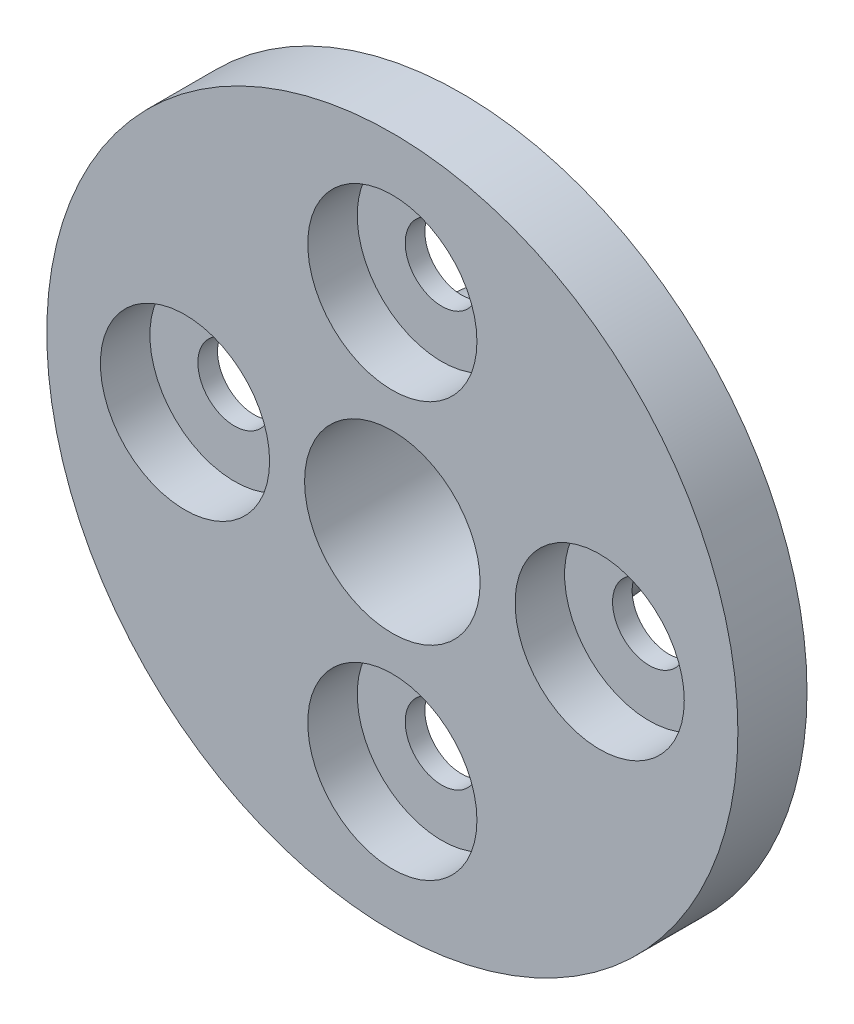
SolidWorks part; units mm, degrees
ref_plane "Alzado" through (0, 0, 0) normal (0, 0, 1) x (1, 0, 0)
ref_plane "Planta" through (0, 0, 0) normal (0, 1, 0) x (1, 0, 0)
ref_plane "Vista lateral" through (0, 0, 0) normal (1, 0, 0) x (0, 0, -1)
sketch "Sketch1" plane through (0, 0, 0) normal (0, 0, 1) x (1, 0, 0)
  circle A0 centre (0, 0) radius 6.35
  circle A1 centre (0, 0) radius 25
  dimension "D1" = 12.7
  dimension "D2" = 50
extrude "Boss-Extrude1" add sketch "Sketch1" along normal blind 5
sketch "Sketch2" plane through (0, 0, 0) normal (0, 0, -1) x (-1, 0, 0)
  circle A0 centre (0, 0) radius 6.35 construction
  circle A1 centre (0, 0) radius 6.35
  circle A2 centre (0, 0) radius 9
  dimension "D1" = 18
extrude "Boss-Extrude2" add sketch "Sketch2" along normal blind 6
hole_wizard "CBORE for M5 Hex Head Bolt1" positions "Sketch3" profile "Sketch5" counterbore size "M5" standard "ANSI Metric"
sketch "Sketch3" plane through (0, 0, 5) normal (0, 0, 1) x (1, 0, 0)
  circle A0 centre (0, 0) radius 15
  point P0 (0, 15)
  point P2 (15, 0)
  point P4 (0, -15)
  point P6 (-15, 0)
  point P14 (15, 0)
  point P15 (0, 15)
  point P16 (-15, 0)
  point P17 (0, -15)
  point P18 (0.5591, 14.9896)
  dimension "D1" = 30
sketch "Sketch5" plane through (0, 15, 5) normal (1, 0, 0) x (0, -1, 0)
  line L0 (0, 0) -> (0, 21.3423)
  line L1 (0, 21.3423) -> (2.65, 19.75)
  line L2 (2.65, 19.75) -> (2.65, 3.58)
  line L3 (2.65, 3.58) -> (6.12, 3.58)
  line L4 (6.12, 3.58) -> (6.12, 0)
  line L5 (6.12, 0) -> (0, 0)
  line L10 (0, 21.3423) -> (-2.65, 19.75) construction
  line L11 (0, -6.35) -> (0, 107.95) construction
  dimension "Hole Dia." = 5.3
  dimension "Hole Depth" = 19.75
  dimension "C'Bore Dia." = 12.24
  dimension "C'Bore Depth" = 3.58
  dimension "Drill Angle" = 118
